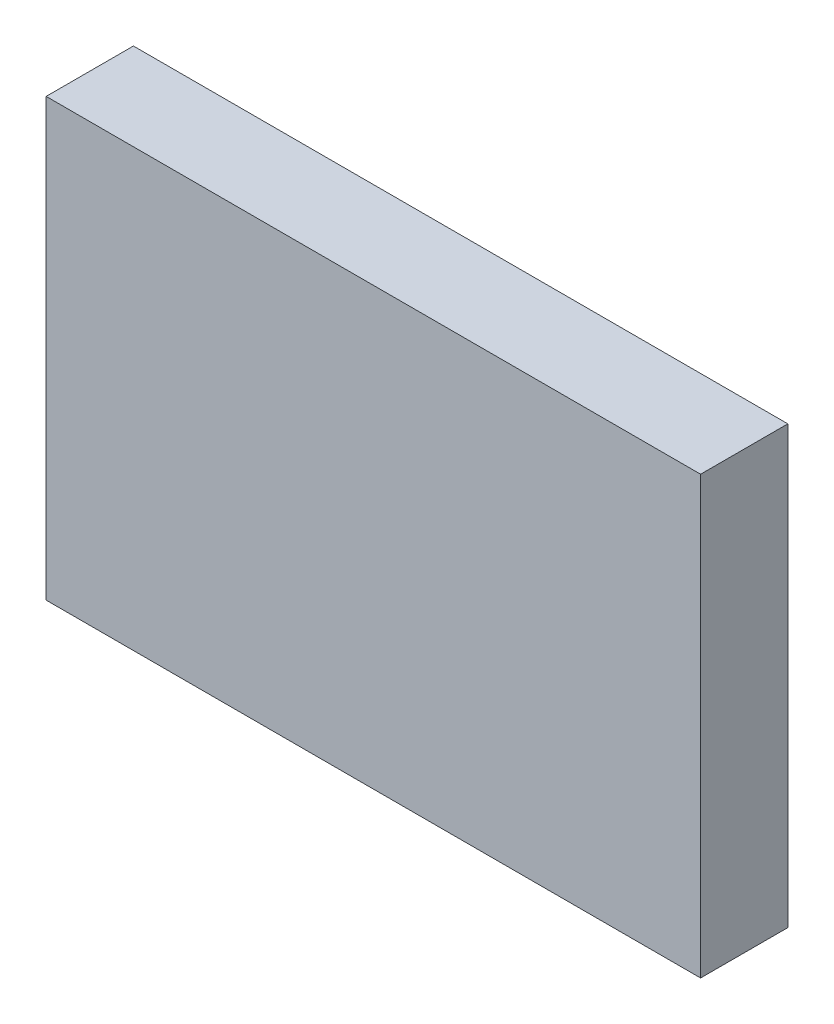
SolidWorks part; units mm, degrees
ref_plane "Alzado" through (0, 0, 0) normal (0, 0, 1) x (1, 0, 0)
ref_plane "Planta" through (0, 0, 0) normal (0, 1, 0) x (1, 0, 0)
ref_plane "Vista lateral" through (0, 0, 0) normal (1, 0, 0) x (0, 0, -1)
sketch "Croquis1" plane through (0, 0, 0) normal (0, 0, 1) x (1, 0, 0)
  line L1 (-30, -20) -> (30, -20)
  line L2 (-30, -20) -> (-30, 20)
  line L3 (-30, 20) -> (30, 20)
  line L4 (30, -20) -> (30, 20)
  line L5 (-30, -20) -> (30, 20) construction
  line L6 (-30, 20) -> (30, -20) construction
  point P0 (0, 0)
  dimension "D1" = 60
  dimension "D2" = 40
extrude "Saliente-Extruir1" add sketch "Croquis1" along normal blind 8
